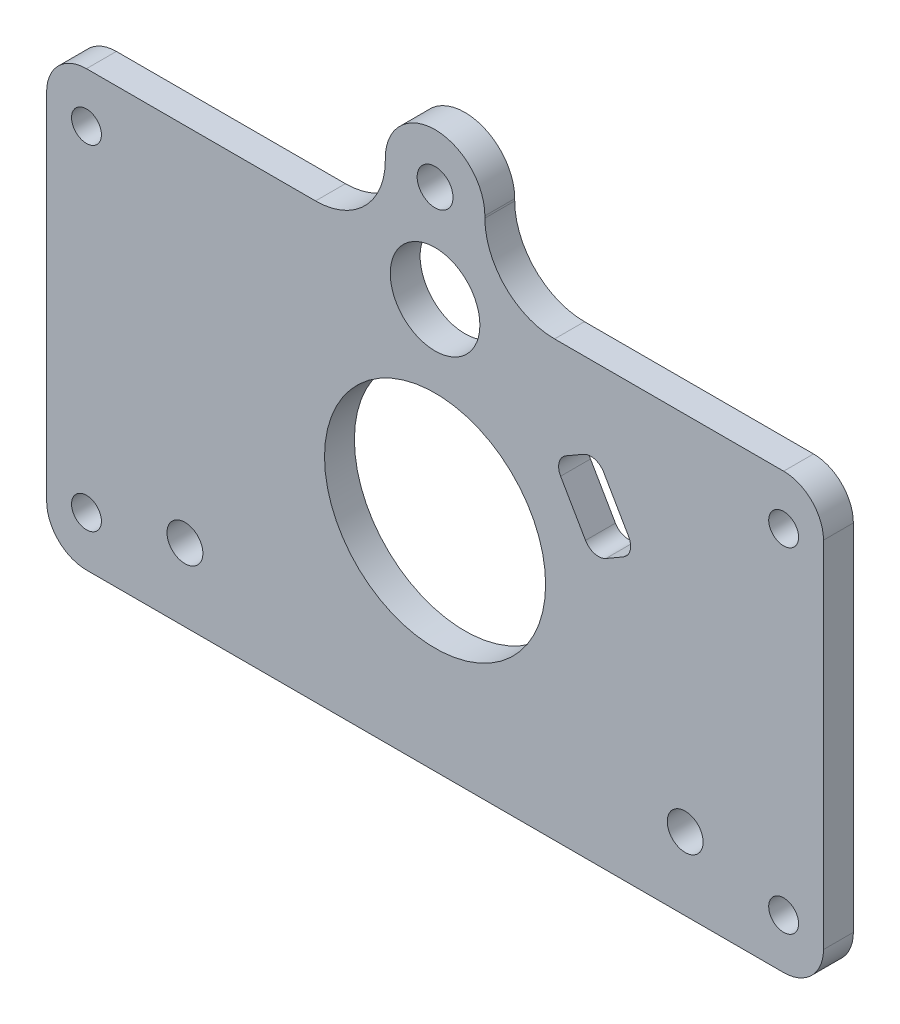
SolidWorks part; units mm, degrees
ref_plane "前视基准面" through (0, 0, 0) normal (0, 0, 1) x (1, 0, 0)
ref_plane "上视基准面" through (0, 0, 0) normal (0, 1, 0) x (1, 0, 0)
ref_plane "右视基准面" through (0, 0, 0) normal (1, 0, 0) x (0, 0, -1)
other "Configuration Table"
sketch "草图1" plane through (0, 0, 0) normal (0, 0, 1) x (1, 0, 0)
  line L13 (-5, 21.8) -> (-5, 29)
  line L14 (-39, -21.8) -> (39, -21.8)
  line L15 (-39, -21.8) -> (-39, 21.8)
  line L16 (-39, 21.8) -> (-5, 21.8)
  line L17 (39, -21.8) -> (39, 21.8)
  line L18 (5, 29) -> (5, 21.8)
  line L19 (5, 21.8) -> (39, 21.8)
  line L20 (11.8564, 11.4641) -> (15.8564, 4.5359)
  line L21 (-35, 16.8) -> (35, 16.8) construction
  line L22 (-35, 16.8) -> (-35, -16.8) construction
  line L23 (-35, -16.8) -> (35, -16.8) construction
  line L24 (35, 16.8) -> (35, -16.8) construction
  line L25 (-35, 16.8) -> (35, -16.8) construction
  line L26 (-35, -16.8) -> (35, 16.8) construction
  line L27 (15.8564, 4.5359) -> (20.1865, 7.0359)
  line L28 (20.1865, 7.0359) -> (16.1865, 13.9641)
  line L29 (16.1865, 13.9641) -> (11.8564, 11.4641)
  circle A0 centre (0, 0) radius 11.1
  circle A21 centre (0, 0) radius 29 construction
  circle A22 centre (0, 29) radius 1.8
  circle A23 centre (25.1147, -14.5) radius 1.8
  circle A24 centre (-25.1147, -14.5) radius 1.8
  arc A25 (-5, 29) -> (5, 29) centre (0, 29) cw
  circle A26 centre (0, 19.25) radius 4.5
  circle A27 centre (35, 16.8) radius 1.5
  circle A28 centre (35, -16.8) radius 1.5
  circle A29 centre (-35, 16.8) radius 1.5
  circle A30 centre (-35, -16.8) radius 1.5
  point P65 (-39, 0)
  dimension "D3" = 22.2
  dimension "D4" = 58
  dimension "D5" = 3.6
  dimension "D6" = 3.6
  dimension "D7" = 3.6
  dimension "D9" = 5
  dimension "D11" = 9
  dimension "D15" = 3
  dimension "D16" = 3
  dimension "D17" = 3
  dimension "D18" = 3
  dimension "D1" = 43.6
  dimension "D2" = 78
  dimension "D8" = 120
  dimension "D10" = 34
  dimension "D12" = 19.25
  dimension "D13" = 70
  dimension "D14" = 33.6
  dimension "D19" = 5
  dimension "D20" = 8
  dimension "D21" = 30
  dimension "D22" = 16
  dimension "D23" = 4
extrude "凸台-拉伸1" add sketch "草图1" along normal blind 3
fillet "圆角1" radius 1.5 4 edges at (20.1865, 7.0359, 1.5) (16.1865, 13.9641, 1.5) (11.8564, 11.4641, 1.5) (15.8564, 4.5359, 1.5)
fillet "圆角2" radius 7 2 edges at (-5, 21.8, 1.5) (5, 21.8, 1.5)
fillet "圆角3" radius 4 4 edges at (39, 21.8, 1.5) (39, -21.8, 1.5) (-39, -21.8, 1.5) (-39, 21.8, 1.5)
